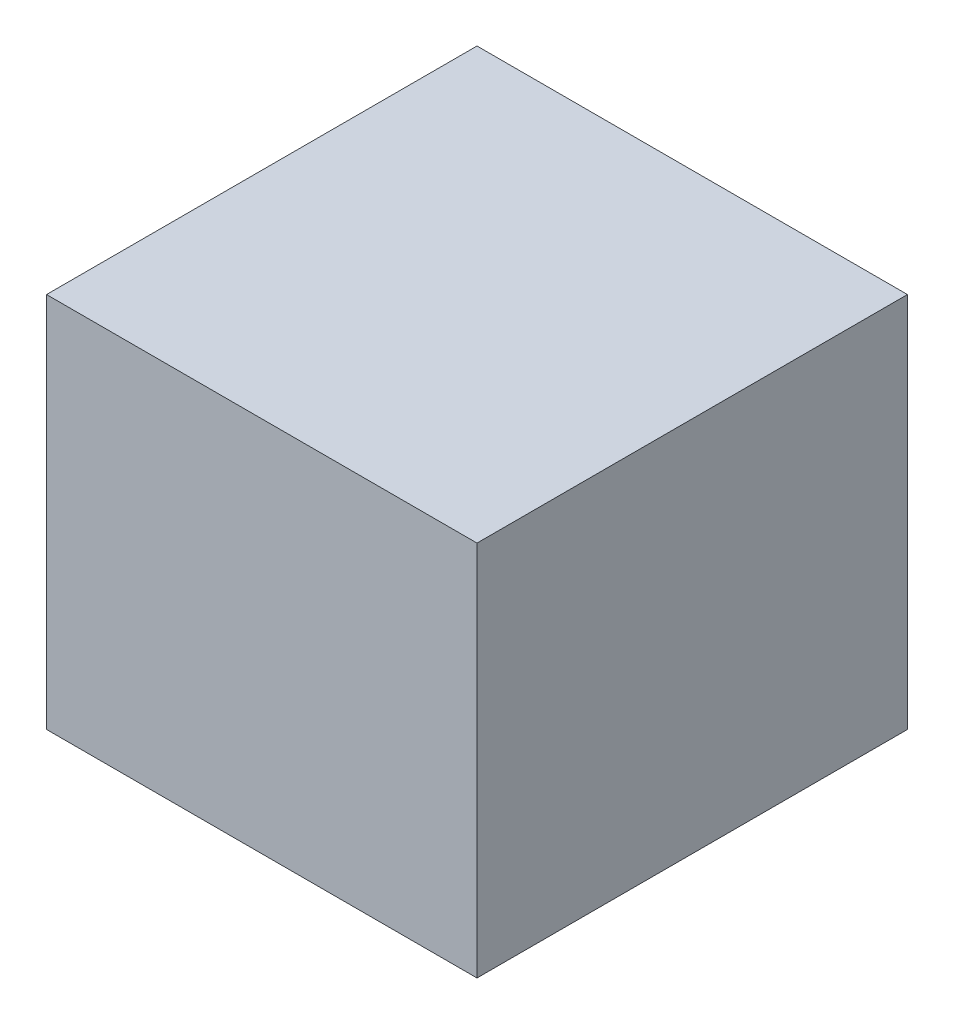
SolidWorks part; units mm, degrees
ref_plane "Спереди" through (0, 0, 0) normal (0, 0, 1) x (1, 0, 0)
ref_plane "Сверху" through (0, 0, 0) normal (0, 1, 0) x (1, 0, 0)
ref_plane "Справа" through (0, 0, 0) normal (1, 0, 0) x (0, 0, -1)
sketch "Эскиз1" plane through (0, 0, 0) normal (0, 1, 0) x (1, 0, 0)
  line L1 (-50.8078, 15.5432) -> (-10.8078, 15.5432)
  line L2 (-50.8078, 15.5432) -> (-50.8078, -24.4568)
  line L3 (-50.8078, -24.4568) -> (-10.8078, -24.4568)
  line L4 (-10.8078, 15.5432) -> (-10.8078, -24.4568)
  dimension "D1" = 40
  dimension "D2" = 40
extrude "Бобышка-Вытянуть1" add sketch "Эскиз1" along normal blind 35
